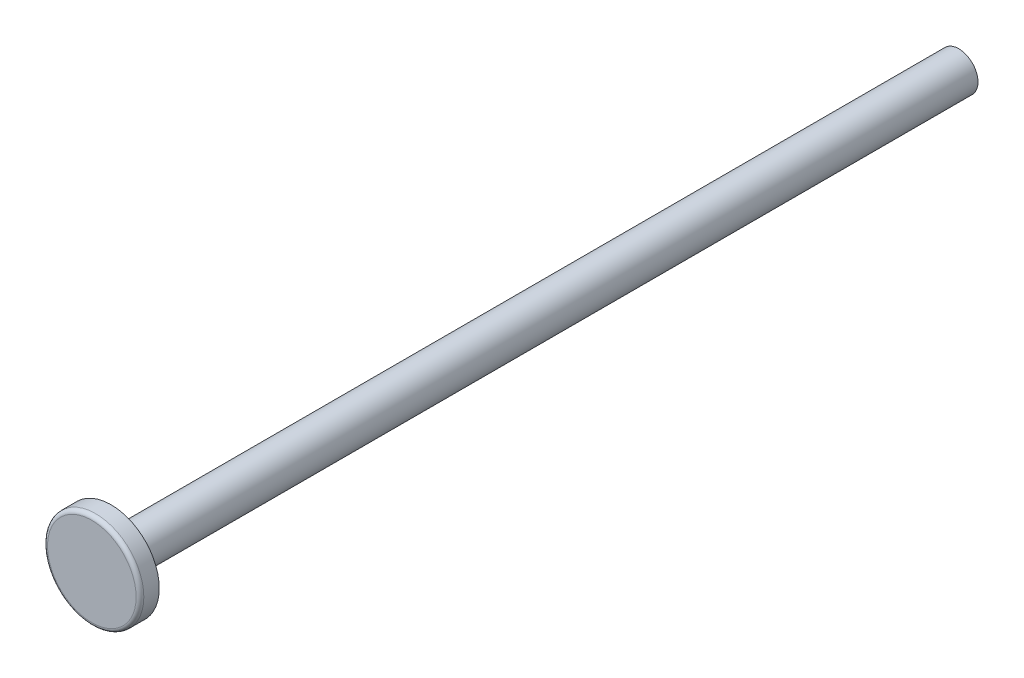
SolidWorks part; units mm, degrees
ref_plane "Front Plane" through (0, 0, 0) normal (0, 0, 1) x (1, 0, 0)
ref_plane "Top Plane" through (0, 0, 0) normal (0, 1, 0) x (1, 0, 0)
ref_plane "Right Plane" through (0, 0, 0) normal (1, 0, 0) x (0, 0, -1)
sketch "Sketch1" plane through (0, 0, 0) normal (0, 0, 1) x (1, 0, 0)
  circle A0 centre (0, 0) radius 5
  dimension "D1" = 10
extrude "Boss-Extrude1" add sketch "Sketch1" along normal mid plane 220
sketch "Sketch2" plane through (0, 0, 110) normal (0, 0, 1) x (1, 0, 0)
  circle A0 centre (0, 0) radius 12.5
  dimension "D1" = 25
extrude "Boss-Extrude2" add sketch "Sketch2" along normal blind 5
fillet "Fillet1" radius 1 1 edges at (12.5, 0, 115)
